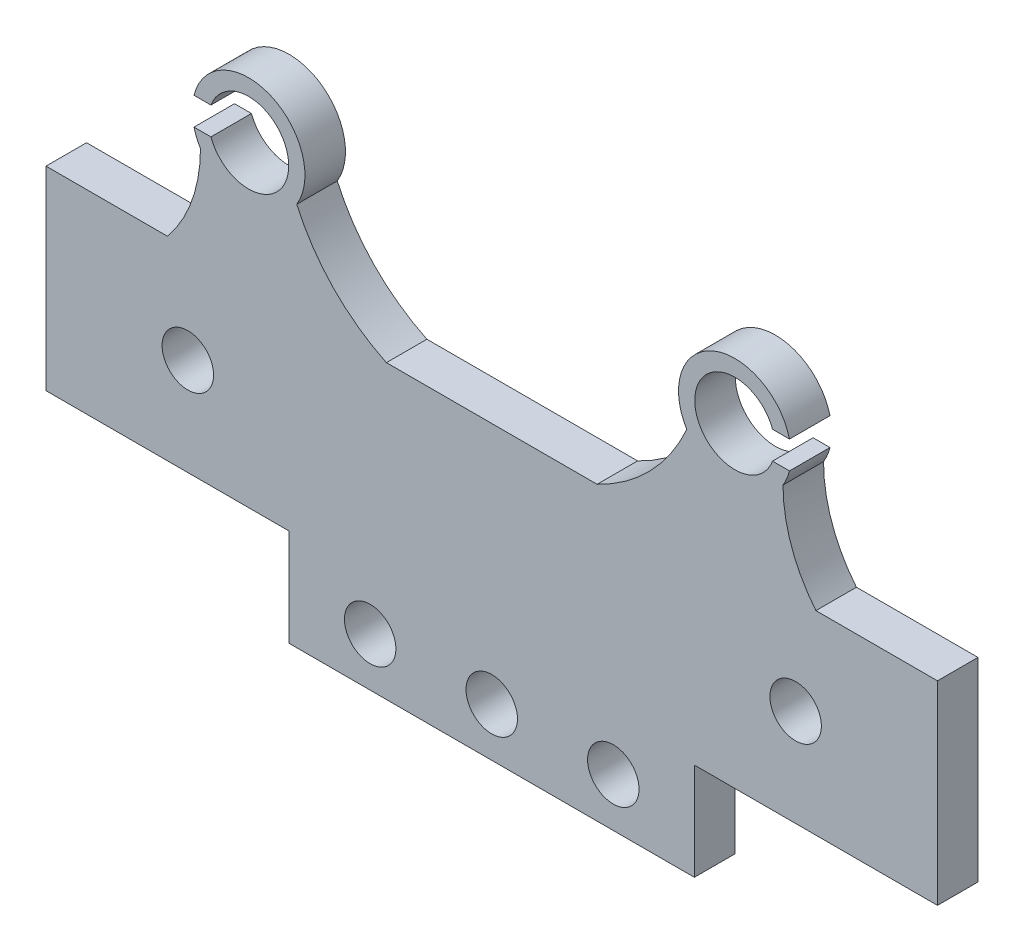
SolidWorks part; units mm, degrees
ref_plane "Alzado" through (0, 0, 0) normal (0, 0, 1) x (1, 0, 0)
ref_plane "Planta" through (0, 0, 0) normal (0, 1, 0) x (1, 0, 0)
ref_plane "Vista lateral" through (0, 0, 0) normal (1, 0, 0) x (0, 0, -1)
sketch "Croquis1" plane through (0, 0, 0) normal (0, 0, 1) x (1, 0, 0)
  line L0 (13, 0) -> (-13, 0)
  line L1 (-55, 0) -> (-55, -24)
  line L2 (-55, -24) -> (-25, -24)
  line L3 (-25, -24) -> (-25, -36)
  line L4 (-25, -36) -> (25, -36)
  line L5 (0, -36) -> (0, 0) construction
  line L6 (-40, 0) -> (-55, 0)
  line L7 (40, 0) -> (55, 0)
  line L8 (55, 0) -> (55, -24)
  line L9 (25, -24) -> (25, -36)
  line L10 (55, -24) -> (25, -24)
  circle A0 centre (-30, 15) radius 4.95
  arc A2 (-24.0615, 11.3894) -> (-35.9385, 11.3894) centre (-30, 15) ccw
  arc A3 (-35.9385, 11.3894) -> (-40, 0) centre (-53.9385, 11.3894) cw
  arc A4 (-24.0615, 11.3894) -> (-13, 0) centre (-3.0454, 20.7342) ccw
  circle A5 centre (-30, 15) radius 6.95 construction
  circle A7 centre (-37.5, -12) radius 3.175
  circle A8 centre (0, -30) radius 3.175
  arc A9 (24.0615, 11.3894) -> (13, 0) centre (3.0454, 20.7342) cw
  circle A10 centre (30, 15) radius 4.95
  arc A11 (24.0615, 11.3894) -> (35.9385, 11.3894) centre (30, 15) cw
  arc A12 (35.9385, 11.3894) -> (40, 0) centre (53.9385, 11.3894) ccw
  circle A13 centre (37.5, -12) radius 3.175
  circle A14 centre (-15, -30) radius 3.175
  circle A15 centre (15, -30) radius 3.175
  point P37 (0, 0)
  dimension "D2" = 9.9
  dimension "D3" = 15
  dimension "D5" = 18
  dimension "D6" = 15
  dimension "D8" = 23
  dimension "D15" = 37.5
  dimension "D14" = 6.35
  dimension "D1" = 2
  dimension "D4" = 30
  dimension "D7" = 55
  dimension "D9" = 13
  dimension "D10" = 24
  dimension "D11" = 30
  dimension "D12" = 12
  dimension "D13" = 12
  dimension "D16" = 30
  dimension "D17" = 10
extrude "Saliente-Extruir1" add sketch "Croquis1" along normal blind 5
sketch "Croquis2" plane through (0, 0, 0) normal (0, 0, 1) x (1, 0, 0)
  line L0 (-30, 15) -> (-36.95, 15) construction
  line L1 (-30, 16.7) -> (-36.7389, 16.7)
  line L2 (-30, 13.3) -> (-36.7389, 13.3)
  line L3 (-30, 13.3) -> (-36.95, 13.3) construction
  line L4 (-30, 16.7) -> (-36.95, 16.7) construction
  line L5 (-30, 16.7) -> (-30, 13.3)
  line L6 (0, 0) -> (0, -26.825) construction
  line L7 (30, 16.7) -> (30, 13.3)
  line L8 (30, 13.3) -> (36.7389, 13.3)
  line L9 (30, 16.7) -> (36.7389, 16.7)
  arc A0 (-24.0615, 11.3894) -> (-35.9385, 11.3894) centre (-30, 15) ccw construction
  arc A1 (-36.7389, 16.7) -> (-36.7389, 13.3) centre (-30, 15) ccw
  circle A2 centre (0, -30) radius 3.175 construction
  arc A3 (36.7389, 16.7) -> (36.7389, 13.3) centre (30, 15) cw
  dimension "D1" = 1.7
  dimension "D2" = 1.7
extrude "Cortar-Extruir1" cut sketch "Croquis2" along normal through all
